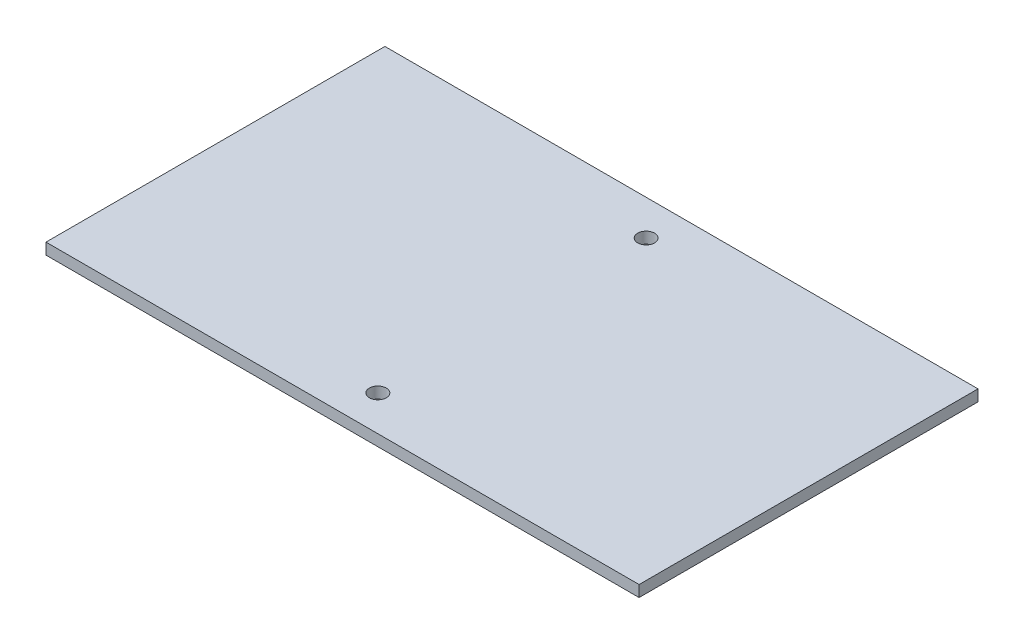
SolidWorks part; units mm, degrees
ref_plane "Front Plane" through (0, 0, 0) normal (0, 0, 1) x (1, 0, 0)
ref_plane "Top Plane" through (0, 0, 0) normal (0, 1, 0) x (1, 0, 0)
ref_plane "Right Plane" through (0, 0, 0) normal (1, 0, 0) x (0, 0, -1)
sketch "Sketch1" plane through (0, 0, 0) normal (0, 1, 0) x (1, 0, 0)
  line L1 (-105, 60) -> (105, 60)
  line L2 (-105, 60) -> (-105, -60)
  line L3 (-105, -60) -> (105, -60)
  line L4 (105, 60) -> (105, -60)
  line L5 (-105, 60) -> (105, -60) construction
  line L6 (-105, -60) -> (105, 60) construction
  point P0 (0, 0)
  dimension "D1" = 210
  dimension "D2" = 120
extrude "Boss-Extrude3" add sketch "Sketch1" along normal blind 4
sketch "Sketch4" plane through (0, 0, 0) normal (0, -1, 0) x (1, 0, 0)
  line L0 (-105, 60) -> (105, 60) construction
  line L1 (-90, 45) -> (90, 45) construction
  line L2 (-90, 45) -> (-90, -45) construction
  line L3 (-90, -45) -> (90, -45) construction
  line L4 (90, 45) -> (90, -45) construction
  line L5 (-90, 45) -> (90, -45) construction
  line L6 (-90, -45) -> (90, 45) construction
  line L7 (-105, -60) -> (-105, 60) construction
  circle A0 centre (-90, 45) radius 4.75
  circle A1 centre (-90, -45) radius 4.75
  circle A2 centre (90, 45) radius 4.75
  circle A3 centre (90, -45) radius 4.75
  point P0 (0, 0)
  dimension "D2" = 9.5
  dimension "D1" = 15
  dimension "6" = 15
sketch "Sketch5" plane through (0, 4, 0) normal (0, 1, 0) x (1, 0, 0)
  line L0 (0, 60) -> (0, -60) construction
  line L1 (105, 60) -> (-105, 60) construction
  line L2 (-105, -60) -> (105, -60) construction
  line L3 (-105, 0) -> (105, 0) construction
  line L4 (-105, 60) -> (-105, -60) construction
  line L5 (105, -60) -> (105, 60) construction
  circle A0 centre (0, 47.5) radius 3
  circle A1 centre (0, -47.5) radius 3
  dimension "D1" = 6
  dimension "D2" = 95
extrude "Cut-Extrude1" cut sketch "Sketch5" against normal blind 10
